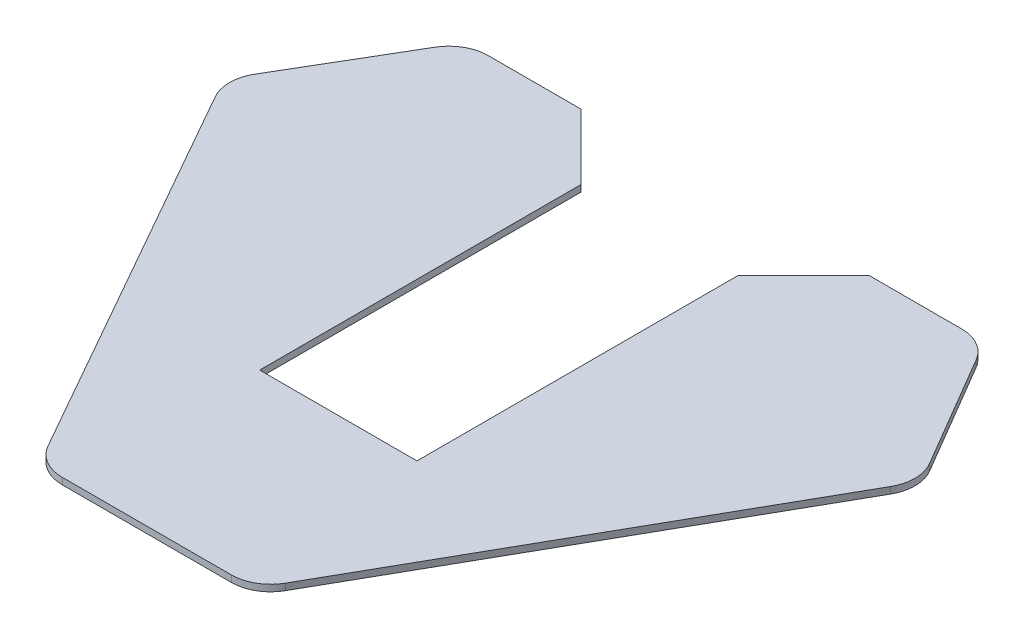
SolidWorks part; units mm, degrees
material "6061 合金"
ref_plane "前视基准面" through (0, 0, 0) normal (0, 0, 1) x (1, 0, 0)
ref_plane "上视基准面" through (0, 0, 0) normal (0, 1, 0) x (1, 0, 0)
ref_plane "右视基准面" through (0, 0, 0) normal (1, 0, 0) x (0, 0, -1)
sketch "草图2" plane through (0, 0, 0) normal (0, 1, 0) x (1, 0, 0)
  line L1 (0, 0) -> (0, 227.8132) construction
  line L16 (-197.7907, 180) -> (-266.1299, 63.7791)
  line L17 (-266.1299, 63.7791) -> (-81.97, -261.14)
  line L18 (-81.97, -261.14) -> (81.97, -261.14)
  line L19 (266.1299, 63.7791) -> (81.97, -261.14)
  line L20 (197.7907, 180) -> (266.1299, 63.7791)
  line L21 (-197.7907, 180) -> (197.7907, 180)
  point P21 (0, 0)
  point P24 (0, 0)
  dimension "D1" = 163.94
  dimension "D2" = 261.14
  dimension "D3" = 373.48
  dimension "D4" = 120
  dimension "D6" = 180
extrude "凸台-拉伸1" add sketch "草图2" along normal blind 5
sketch "草图3" plane through (0, 5, 0) normal (0, 1, 0) x (1, 0, 0)
  line L0 (197.7907, 180) -> (-197.7907, 180) construction
  line L1 (170.1546, 180) -> (-197.7907, 180) construction
  line L2 (0, 0) -> (0, 224.588) construction
  line L3 (110, 180) -> (25, 95)
  line L4 (25, 95) -> (-25, 95)
  line L5 (-110, 180) -> (-25, 95)
  point P10 (0, 95)
  dimension "D1" = 45
  dimension "D2" = 85
  dimension "D3" = 220
extrude "切除-拉伸1" cut sketch "草图3" against normal through all and the other way through all
sketch "草图4" plane through (0, 5, 0) normal (0, 1, 0) x (1, 0, 0)
  line L0 (0, 0) -> (0, 329.8602) construction
  line L2 (-60, -115) -> (60, -115)
  line L3 (-60, -115) -> (-60, 245)
  line L4 (-60, 245) -> (60, 245)
  line L5 (60, -115) -> (60, 245)
  line L6 (-60, -115) -> (60, 245) construction
  line L7 (-60, 245) -> (60, -115) construction
  point P3 (0, 65)
  dimension "D1" = 120
  dimension "D2" = 115
extrude "切除-拉伸2" cut sketch "草图4" against normal up to next
fillet "圆角1" radius 30 6 edges at (197.7907, 2.5, -180) (266.1299, 2.5, -63.7791) (81.97, 2.5, 261.14) (-81.97, 2.5, 261.14) (-266.1299, 2.5, -63.7791) (-197.7907, 2.5, -180)
